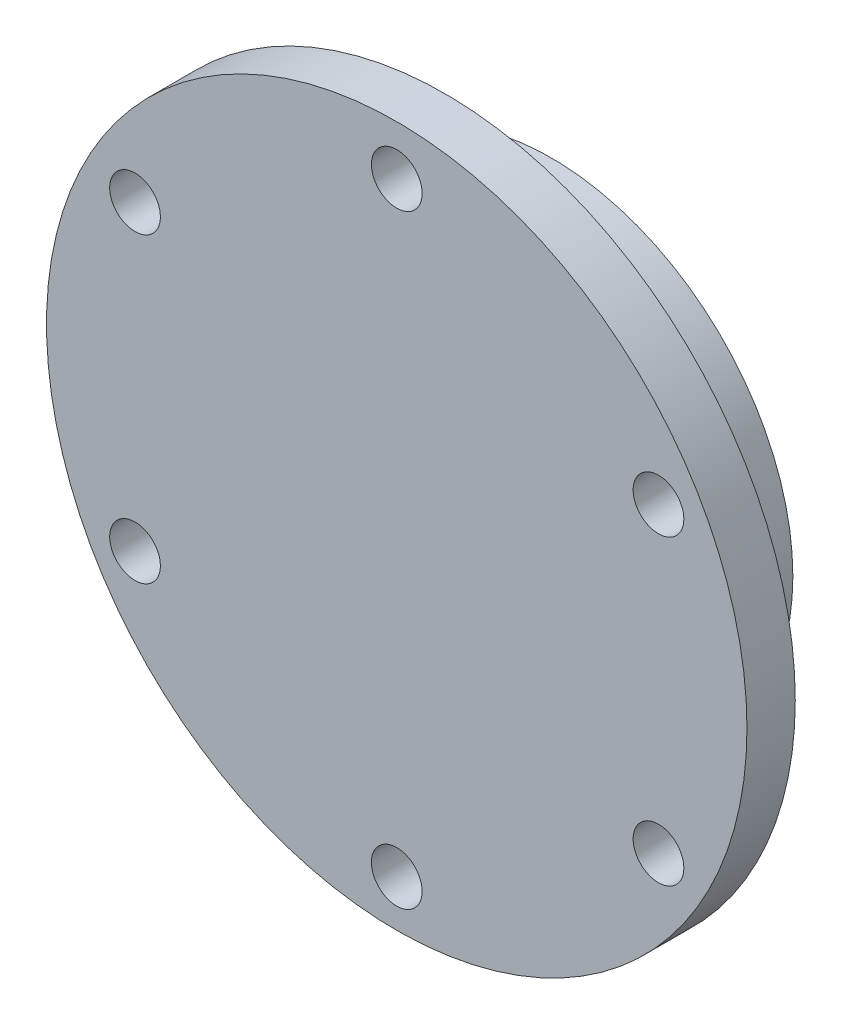
SolidWorks part; units mm, degrees
ref_plane "Alzado" through (0, 0, 0) normal (0, 0, 1) x (1, 0, 0)
ref_plane "Planta" through (0, 0, 0) normal (0, 1, 0) x (1, 0, 0)
ref_plane "Vista lateral" through (0, 0, 0) normal (1, 0, 0) x (0, 0, -1)
sketch "Croquis1" plane through (0, 0, 0) normal (0, 0, 1) x (1, 0, 0)
  circle A0 centre (0, 0) radius 72.5
  dimension "D1" = 145
extrude "Saliente-Extruir1" add sketch "Croquis1" along normal blind 10
sketch "Croquis3" plane through (0, 0, 10) normal (0, 0, 1) x (1, 0, 0)
  circle A0 centre (0, 0) radius 62.5
  dimension "D1" = 125
sketch "Croquis10" plane through (0, 0, 0) normal (0, 0, -1) x (-1, 0, 0)
  line L0 (0, 0) -> (0, 89.2963)
hole_wizard "Perforador para roscar para macho de roscar para M12x1.51" positions "Croquis3D5" profile "Croquis12" hole size "M12x1.5" standard "Ansi Metric"
sketch3d "Croquis3D5"
  line L0 (0, 0, 0) -> (0, 89.2963, 0) construction
  point P0 (0, 62.2336, 0)
sketch "Croquis12" plane through (0, 62.2336, 0) normal (1, 0, 0) x (0, 1, 0)
  line L0 (0, 0) -> (0, 46.6545)
  line L1 (0, 46.6545) -> (5.25, 43.5)
  line L2 (5.25, 43.5) -> (5.25, 0)
  line L5 (5.25, 0) -> (0, 0)
  line L10 (0, 46.6545) -> (-5.25, 43.5) construction
  line L11 (0, -6.35) -> (0, 107.95) construction
  dimension "Diámetro de taladro" = 10.5
  dimension "Profundidad de taladro" = 43.5
  dimension "Ángulo de perforador" = 118
pattern_circular "MatrizC3" count 6 over 360 about axis through (0, -0.3281, 0) along (0, 0, 1) of "Perforador para roscar para macho de roscar para M12x1.51"
sketch "Croquis13" plane through (0, 0, 0) normal (0, 0, -1) x (-1, 0, 0)
  circle A0 centre (0, 0) radius 50
  dimension "D1" = 100
extrude "Saliente-Extruir2" add sketch "Croquis13" along normal blind 22
